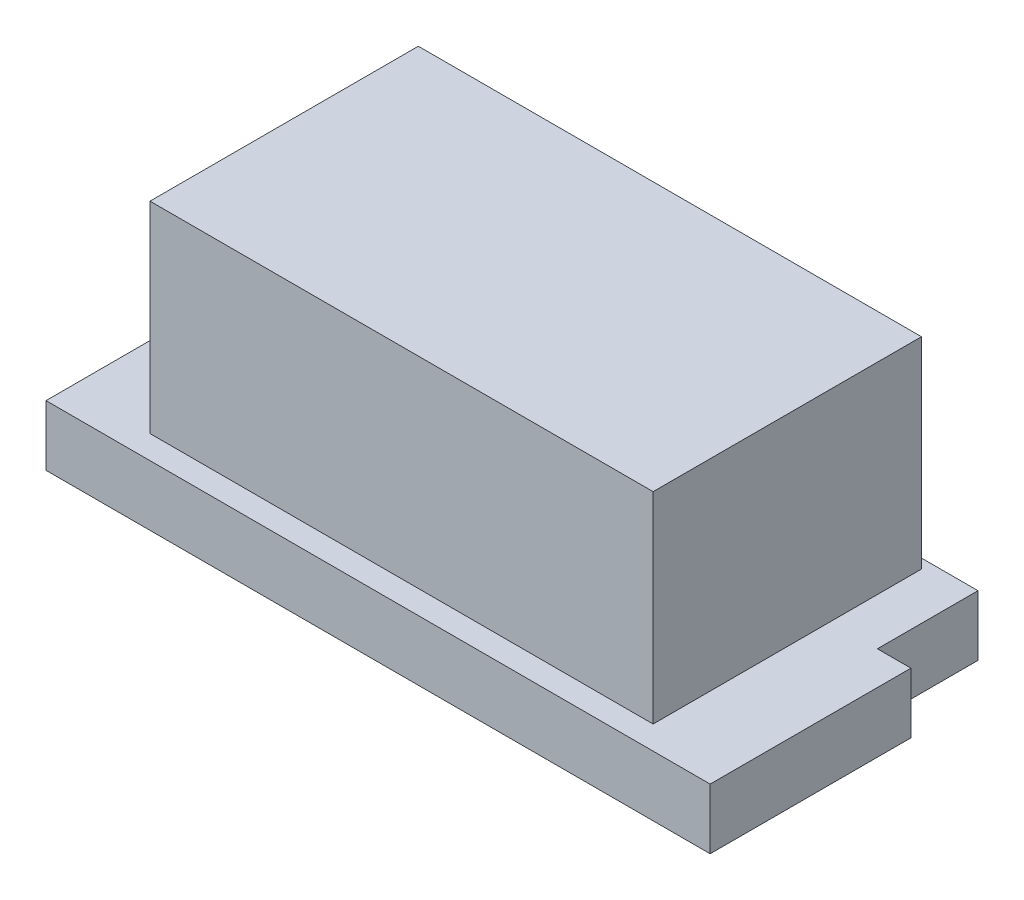
SolidWorks part; units mm, degrees
ref_plane "前视基准面" through (0, 0, 0) normal (0, 0, 1) x (1, 0, 0)
ref_plane "上视基准面" through (0, 0, 0) normal (0, 1, 0) x (1, 0, 0)
ref_plane "右视基准面" through (0, 0, 0) normal (1, 0, 0) x (0, 0, -1)
sketch "草图1" plane through (0, 0, 0) normal (0, 1, 0) x (1, 0, 0)
  line L1 (0, 0) -> (-19.8, 0)
  line L2 (0, 0) -> (0, 9.8)
  line L3 (0, 9.8) -> (-19.8, 9.8)
  line L4 (-19.8, 0) -> (-19.8, 9.8)
extrude "凸台-拉伸1" add sketch "草图1" along normal blind 1.8
sketch "草图2" plane through (0, 1.8, 0) normal (0, 1, 0) x (1, 0, 0)
  line L1 (-2.4, 0.7) -> (-17.4, 0.7)
  line L2 (-2.4, 0.7) -> (-2.4, 8.7)
  line L3 (-2.4, 8.7) -> (-17.4, 8.7)
  line L4 (-17.4, 0.7) -> (-17.4, 8.7)
extrude "凸台-拉伸2" add sketch "草图2" along normal blind 6
sketch "草图3" plane through (0, 1.8, 0) normal (0, 1, 0) x (1, 0, 0)
  line L0 (0, 9.8) -> (-19.8, 9.8) construction
  line L1 (-19.8, 9.8) -> (-18.8, 9.8)
  line L2 (-19.8, 9.8) -> (-19.8, 6.8)
  line L3 (-19.8, 6.8) -> (-18.8, 6.8)
  line L4 (-18.8, 9.8) -> (-18.8, 6.8)
  line L5 (-19.8, 9.8) -> (-19.8, 0) construction
extrude "切除-拉伸1" cut sketch "草图3" against normal blind 3
sketch "草图4" plane through (0, 1.8, 0) normal (0, 1, 0) x (1, 0, 0)
  line L0 (0, 0) -> (0, 9.8) construction
  line L1 (-19.16, 9.9354) -> (0, 9.9354)
  line L2 (-19.16, 9.9354) -> (-19.16, 8.9854)
  line L3 (-19.16, 8.9854) -> (0, 8.9854)
  line L4 (0, 9.9354) -> (0, 8.9854)
extrude "切除-拉伸2" cut sketch "草图4" against normal blind 3
sketch "草图7" plane through (0, 1.8, 0) normal (0, 1, 0) x (1, 0, 0)
  line L1 (0, 8.9854) -> (-1, 8.9854)
  line L2 (0, 8.9854) -> (0, 5.9854)
  line L3 (0, 5.9854) -> (-1, 5.9854)
  line L4 (-1, 8.9854) -> (-1, 5.9854)
extrude "切除-拉伸4" cut sketch "草图7" against normal blind 3
